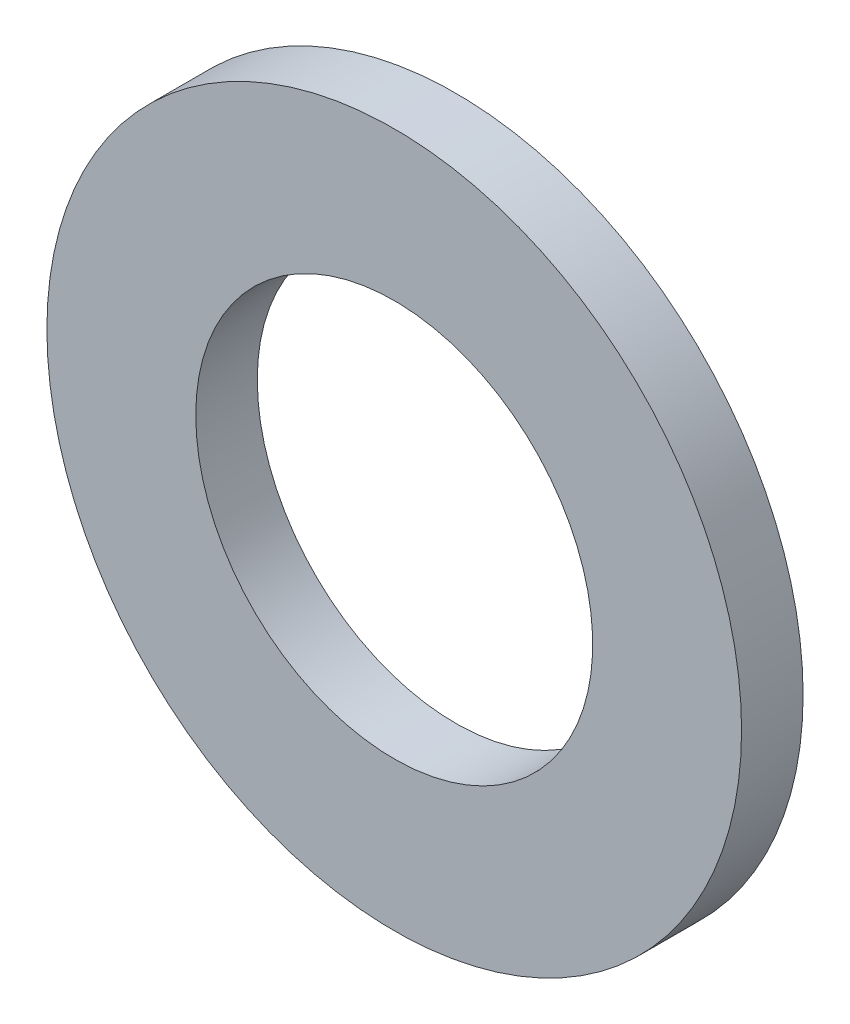
SolidWorks part; units mm, degrees
material "ABS"
ref_plane "前视基准面" through (0, 0, 0) normal (0, 0, 1) x (1, 0, 0)
ref_plane "上视基准面" through (0, 0, 0) normal (0, 1, 0) x (1, 0, 0)
ref_plane "右视基准面" through (0, 0, 0) normal (1, 0, 0) x (0, 0, -1)
other "Configuration Table"
sketch "草图1" plane through (0, 0, 0) normal (0, 0, 1) x (1, 0, 0)
  circle A0 centre (0, 0) radius 10
  circle A1 centre (0, 0) radius 17.5
  dimension "D1" = 35
  dimension "D2" = 20
extrude "凸台-拉伸1" add sketch "草图1" along normal blind 3.1
